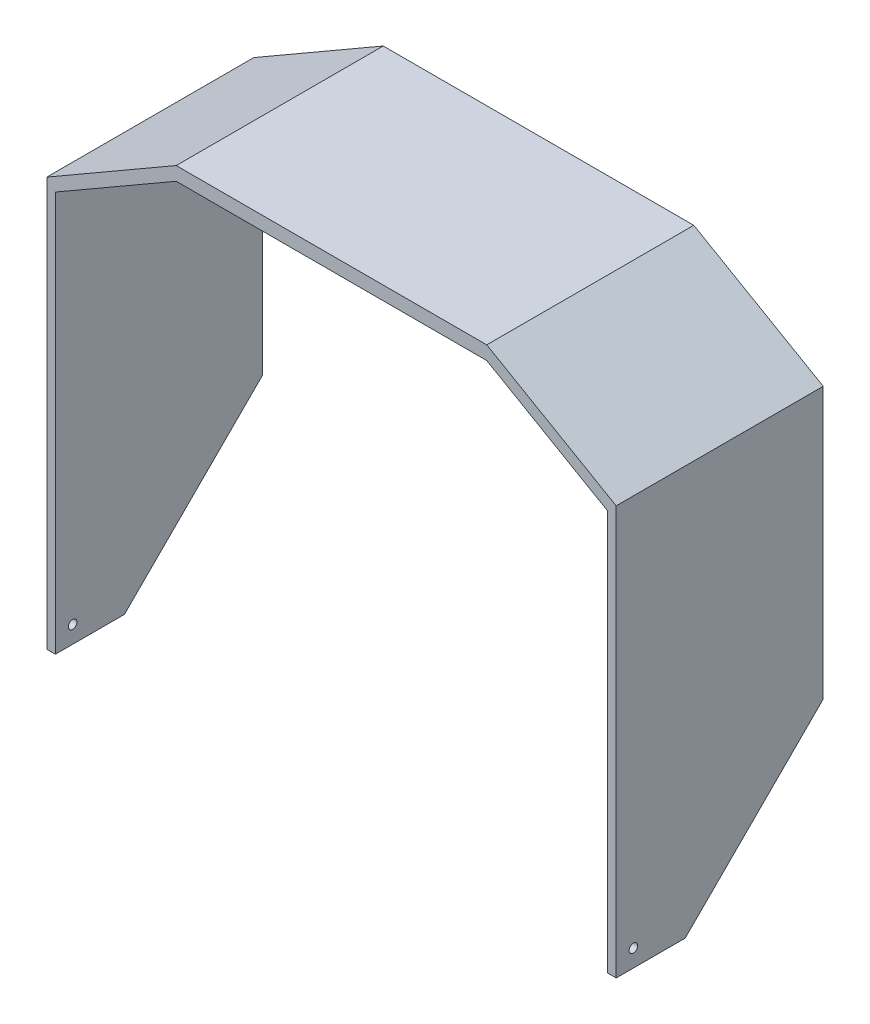
SolidWorks part; units mm, degrees
ref_plane "Front Plane" through (0, 0, 0) normal (0, 0, 1) x (1, 0, 0)
ref_plane "Top Plane" through (0, 0, 0) normal (0, 1, 0) x (1, 0, 0)
ref_plane "Right Plane" through (0, 0, 0) normal (1, 0, 0) x (0, 0, -1)
sketch "Sketch3" plane through (0, 0, 0) normal (0, 0, 1) x (1, 0, 0)
  line L0 (-5, 5) -> (-5, -232)
  line L2 (0, 0) -> (0, -232)
  line L4 (320, 0) -> (320, -232)
  line L6 (325, 5) -> (325, -232)
  line L7 (325, -232) -> (320, -232)
  line L8 (0, -232) -> (-5, -232)
  line L9 (0, 0) -> (70, 40.4145)
  line L10 (0, 0) -> (320, 0) construction
  line L11 (-5, 5) -> (325, 5) construction
  line L12 (70, 40.4145) -> (250, 40.4145)
  line L13 (250, 40.4145) -> (320, 0)
  line L14 (325, 5) -> (250, 48.3013)
  line L15 (250, 48.3013) -> (70, 48.3013)
  line L16 (70, 48.3013) -> (-5, 5)
  dimension "D1" = 320
  dimension "D2" = 232
  dimension "D4" = 120
  dimension "D5" = 120
  dimension "D6" = 70
  dimension "D7" = 120
  dimension "D8" = 120
  dimension "D3" = 5
extrude "Boss-Extrude2" add sketch "Sketch3" along normal blind 120
sketch "Sketch5" plane through (325, 0, 0) normal (1, 0, 0) x (0, 0, -1)
  line L0 (-120, -232) -> (0, -232) construction
  line L1 (-120, -232) -> (-120, 5) construction
  line L2 (-80, -232) -> (0, -152)
  line L3 (0, -232) -> (0, 5) construction
  line L4 (0, -152) -> (0, -232)
  line L5 (0, -232) -> (-80, -232)
  circle A0 centre (-110, -222) radius 2.5
  dimension "D1" = 10
  dimension "D3" = 5
  dimension "D2" = 10
  dimension "D4" = 80
extrude "Cut-Extrude2" cut sketch "Sketch5" against normal through all both and the other way through all
